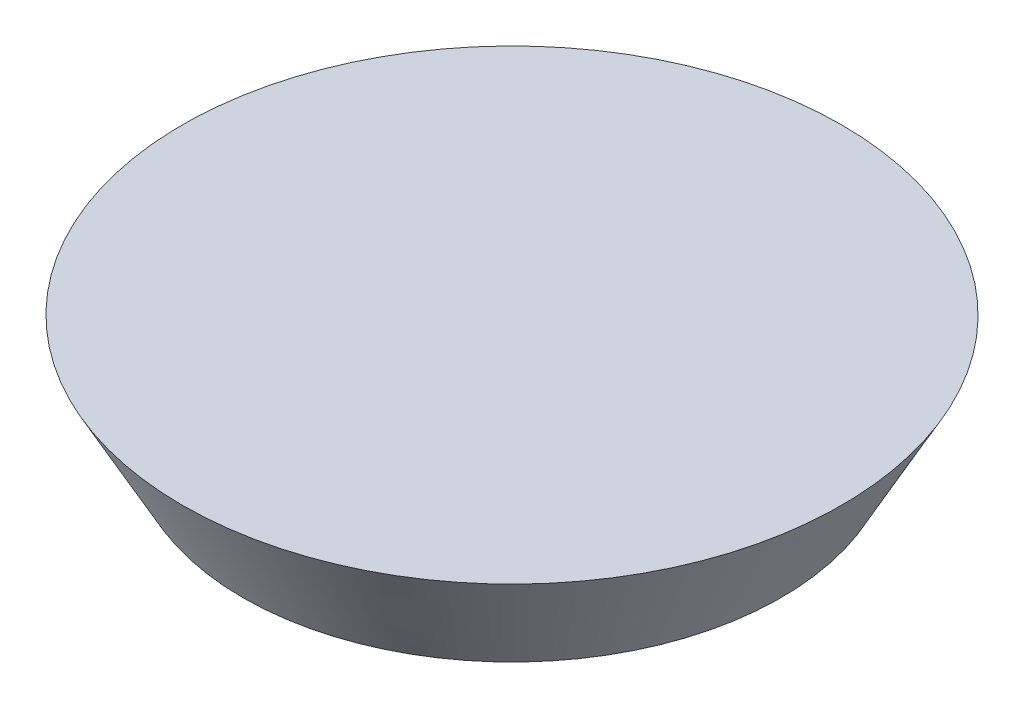
SolidWorks part; units mm, degrees
ref_plane "Front Plane" through (0, 0, 0) normal (0, 0, 1) x (1, 0, 0)
ref_plane "Top Plane" through (0, 0, 0) normal (0, 1, 0) x (1, 0, 0)
ref_plane "Right Plane" through (0, 0, 0) normal (1, 0, 0) x (0, 0, -1)
sketch "Sketch2" plane through (0, 0, 0) normal (0, 0, 1) x (1, 0, 0)
  line L0 (0, 0) -> (0, -15.7618) construction
  line L1 (0, 0) -> (-10, 0)
  line L2 (-10, 0) -> (-12.25, 4.1)
  line L3 (-12.25, 4.1) -> (0, 4.1)
  line L4 (0, 4.1) -> (0, 0)
  dimension "D1" = 24.5
  dimension "D2" = 20
  dimension "D3" = 4.1
revolve "Revolve1" add sketch "Sketch2" angle 360 about L0
equation "\"BottomDiameter\" = 20"
equation "\"D2@Sketch2\"=\"BottomDiameter\""
equation "\"TopDiameter\"=24.5"
equation "\"D1@Sketch2\"=\"TopDiameter\""
equation "\"Thicknes\"= 4.1"
equation "\"D3@Sketch2\"=\"Thicknes\""
